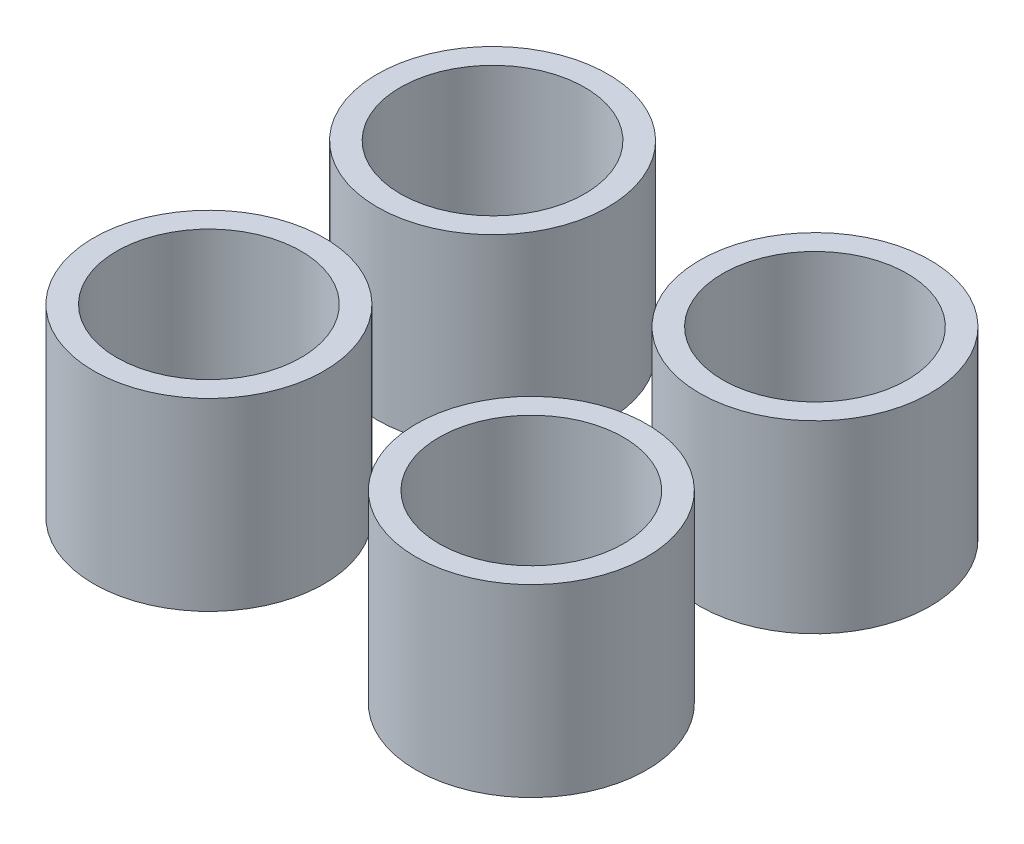
SolidWorks part; units mm, degrees
ref_plane "Front Plane" through (0, 0, 0) normal (0, 0, 1) x (1, 0, 0)
ref_plane "Top Plane" through (0, 0, 0) normal (0, 1, 0) x (1, 0, 0)
ref_plane "Right Plane" through (0, 0, 0) normal (1, 0, 0) x (0, 0, -1)
sketch "Sketch1" plane through (0, 0, 0) normal (0, 1, 0) x (1, 0, 0)
  circle A0 centre (0, 0) radius 2.5
  circle A1 centre (-6.9921, 0) radius 2.5
  circle A2 centre (-6.9921, -6.1515) radius 2.5
  circle A3 centre (0, -6.1515) radius 2.5
  dimension "D1" = 5
  dimension "D2" = 5
  dimension "D3" = 5
  dimension "D4" = 5
extrude "Boss-Extrude1" add sketch "Sketch1" along normal blind 4
sketch "Sketch2" plane through (0, 4, 0) normal (0, 1, 0) x (1, 0, 0)
  circle A0 centre (-6.9921, 0) radius 2
  circle A1 centre (0, 0) radius 2
  circle A2 centre (-6.9921, -6.1515) radius 2
  circle A3 centre (0, -6.1515) radius 2
  dimension "D1" = 4
  dimension "D2" = 4
  dimension "D3" = 4
  dimension "D4" = 4
extrude "Cut-Extrude1" cut sketch "Sketch2" against normal blind 5
